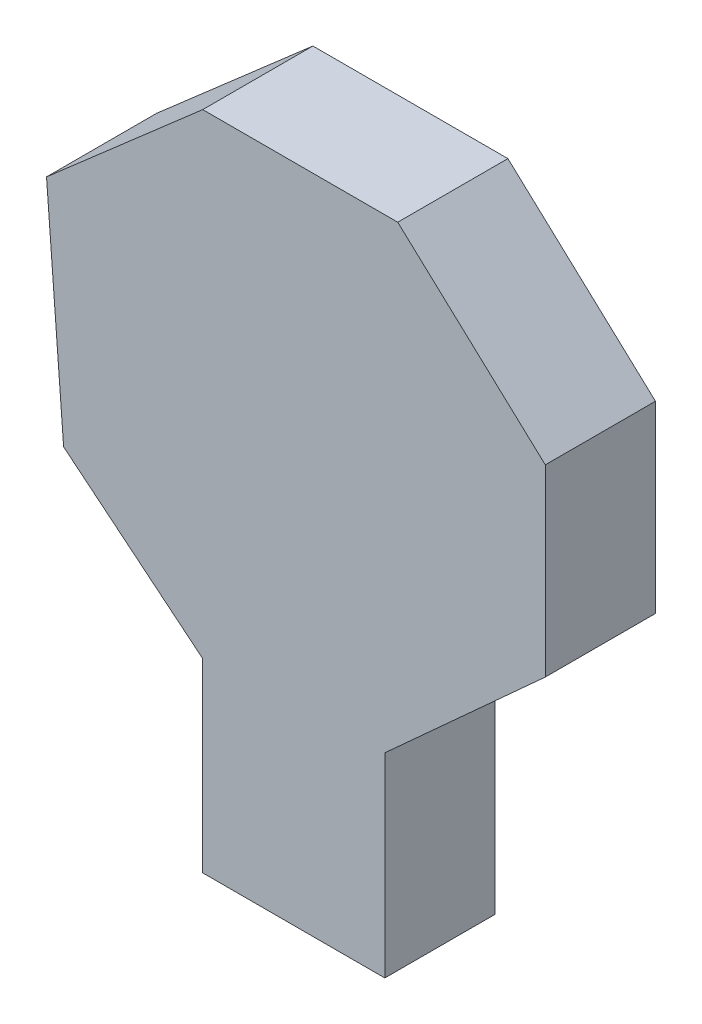
SolidWorks part; units mm, degrees
ref_plane "前视基准面" through (0, 0, 0) normal (0, 0, 1) x (1, 0, 0)
ref_plane "上视基准面" through (0, 0, 0) normal (0, 1, 0) x (1, 0, 0)
ref_plane "右视基准面" through (0, 0, 0) normal (1, 0, 0) x (0, 0, -1)
sketch "草图1" plane through (0, 0, 0) normal (0, 0, 1) x (1, 0, 0)
  line L0 (-8.4204, -0.8616) -> (-8.4204, -17.7023)
  line L1 (-8.4204, -17.7023) -> (8.107, -17.7023)
  line L2 (8.107, -17.7023) -> (8.107, 0)
  line L3 (8.107, 0) -> (22.6762, 13.2376)
  line L4 (22.6762, 13.2376) -> (22.6762, 29.9217)
  line L5 (22.6762, 29.9217) -> (9.282, 42.2977)
  line L6 (9.282, 42.2977) -> (-8.4204, 42.2977)
  line L7 (-8.4204, 42.2977) -> (-22.5979, 29.9217)
  line L8 (-22.5979, 29.9217) -> (-21.0464, 9.4739)
  line L9 (-21.0464, 9.4739) -> (-8.4204, -0.8616)
  dimension "D1" = 60
extrude "凸台-拉伸1" add sketch "草图1" along normal blind 10
